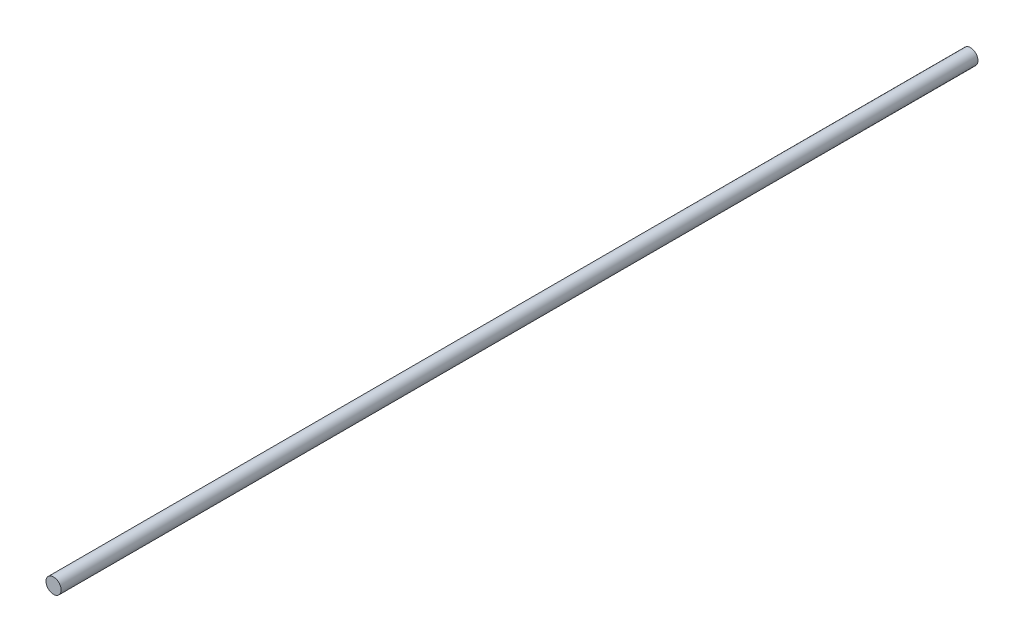
SolidWorks part; units mm, degrees
ref_plane "Front Plane" through (0, 0, 0) normal (0, 0, 1) x (1, 0, 0)
ref_plane "Top Plane" through (0, 0, 0) normal (0, 1, 0) x (1, 0, 0)
ref_plane "Right Plane" through (0, 0, 0) normal (1, 0, 0) x (0, 0, -1)
sketch "Sketch1" plane through (0, 0, 0) normal (0, 0, 1) x (1, 0, 0)
  circle A0 centre (0, 0) radius 4
  dimension "D1" = 8
extrude "Boss-Extrude1" add sketch "Sketch1" along normal blind 485
ref_plane "Plane1" through (0, 0, 242.5) normal (0, 0, 1) x (1, 0, 0)
